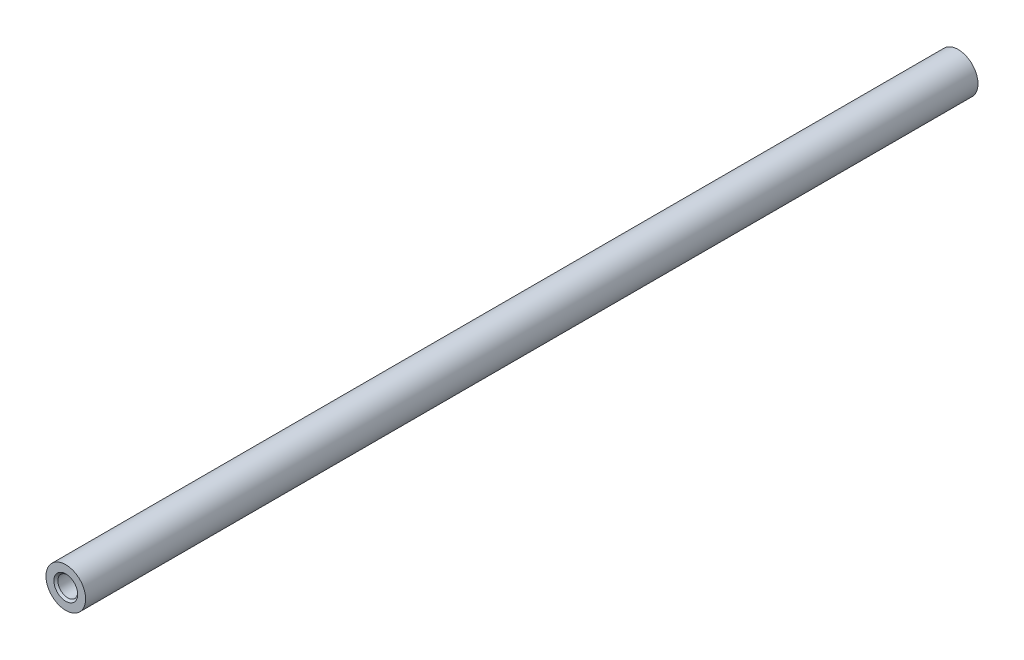
SolidWorks part; units mm, degrees
ref_plane "정면" through (0, 0, 0) normal (0, 0, 1) x (1, 0, 0)
ref_plane "윗면" through (0, 0, 0) normal (0, 1, 0) x (1, 0, 0)
ref_plane "우측면" through (0, 0, 0) normal (1, 0, 0) x (0, 0, -1)
sketch "스케치2" plane through (0, 0, 0) normal (0, 0, 1) x (1, 0, 0)
  circle A0 centre (0, 0) radius 10
  circle A1 centre (0, 0) radius 5
  dimension "D1" = 20
  dimension "D2" = 10
extrude "보스-돌출1" add sketch "스케치2" along normal blind 450
chamfer "모따기1" distance 1 angle 45 1 edges at (5, 0, 450)
